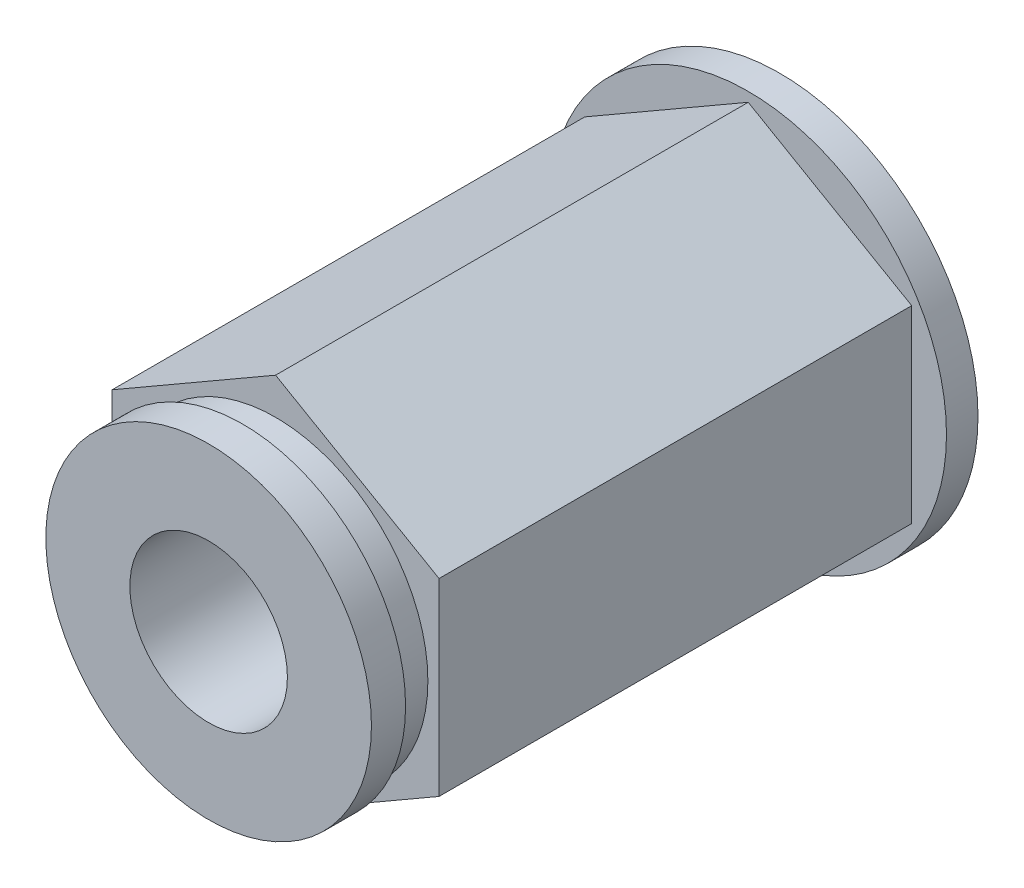
SolidWorks part; units mm, degrees
ref_plane "Plan de face" through (0, 0, 0) normal (0, 0, 1) x (1, 0, 0)
ref_plane "Plan de dessus" through (0, 0, 0) normal (0, 1, 0) x (1, 0, 0)
ref_plane "Plan de droite" through (0, 0, 0) normal (1, 0, 0) x (0, 0, -1)
sketch "Esquisse1" plane through (0, 0, 0) normal (0, 0, 1) x (1, 0, 0)
  circle A0 centre (0, 0) radius 7.55
  dimension "D1" = 15.1
extrude "Boss.-Extru.1" add sketch "Esquisse1" along normal blind 1.2
sketch "Esquisse2" plane through (0, 0, 1.2) normal (0, 0, 1) x (1, 0, 0)
  line L1 (6.225, -3.594) -> (6.225, 3.594)
  line L2 (6.225, 3.594) -> (0, 7.188)
  line L3 (0, 7.188) -> (-6.225, 3.594)
  line L4 (-6.225, 3.594) -> (-6.225, -3.594)
  line L5 (-6.225, -3.594) -> (0, -7.188)
  line L6 (0, -7.188) -> (6.225, -3.594)
  circle A0 centre (0, 0) radius 6.225 construction
  dimension "D1" = 12.45
extrude "Boss.-Extru.2" add sketch "Esquisse2" along normal blind 18
sketch "Esquisse3" plane through (0, 0, 19.2) normal (0, 0, 1) x (1, 0, 0)
  circle A0 centre (0, 0) radius 5.8
  dimension "D1" = 11.6
extrude "Boss.-Extru.3" add sketch "Esquisse3" along normal blind 1.25
sketch "Esquisse4" plane through (0, 0, 20.45) normal (0, 0, 1) x (1, 0, 0)
  circle A0 centre (0, 0) radius 6.2
  dimension "D1" = 12.4
extrude "Boss.-Extru.4" add sketch "Esquisse4" along normal blind 1.3
sketch "Esquisse5" plane through (0, 0, 21.75) normal (0, 0, 1) x (1, 0, 0)
  circle A0 centre (0, 0) radius 3
  dimension "D1" = 6
extrude "Enlèv. mat.-Extru.1" cut sketch "Esquisse5" against normal through all
